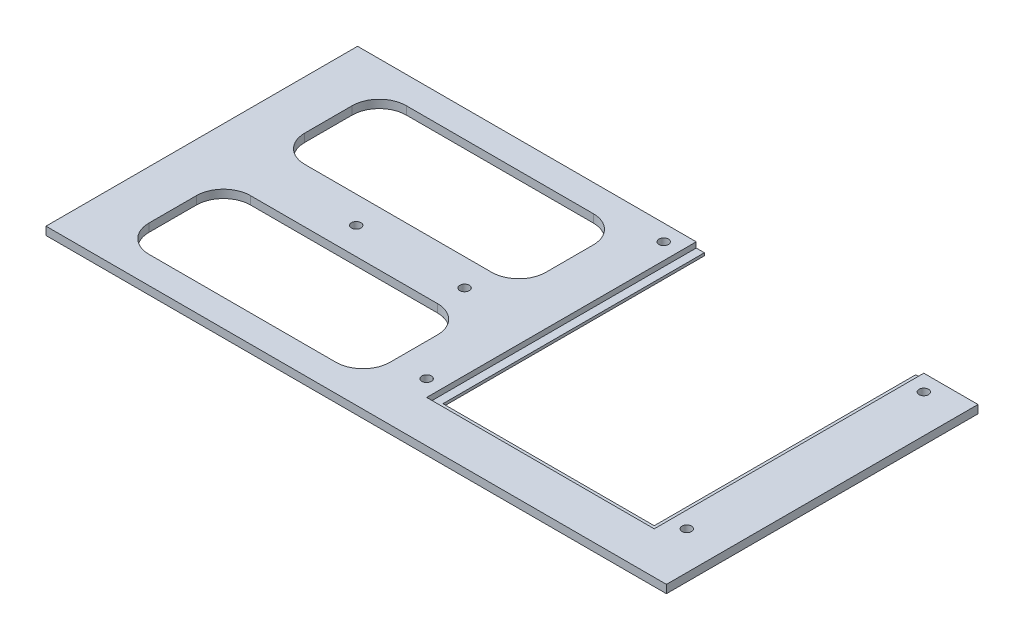
SolidWorks part; units mm, degrees
ref_plane "前视基准面" through (0, 0, 0) normal (0, 0, 1) x (1, 0, 0)
ref_plane "上视基准面" through (0, 0, 0) normal (0, 1, 0) x (1, 0, 0)
ref_plane "右视基准面" through (0, 0, 0) normal (1, 0, 0) x (0, 0, -1)
sketch "草图1" plane through (0, 0, 0) normal (0, 1, 0) x (1, 0, 0)
  line L1 (-121.6849, 60.5367) -> (107.3151, 60.5367)
  line L2 (-121.6849, 60.5367) -> (-121.6849, -54.4633)
  line L3 (-121.6849, -54.4633) -> (107.3151, -54.4633)
  line L4 (107.3151, 60.5367) -> (107.3151, -54.4633)
  dimension "D1" = 229
  dimension "D2" = 115
extrude "凸台-拉伸1" add sketch "草图1" along normal blind 3
sketch "草图2" plane through (0, 3, 0) normal (0, 1, 0) x (1, 0, 0)
  line L0 (107.3151, -54.4633) -> (107.3151, 60.5367) construction
  line L1 (3.3151, 45.0367) -> (87.3151, 45.0367) construction
  line L2 (3.3151, 45.0367) -> (3.3151, -38.9633) construction
  line L3 (3.3151, -38.9633) -> (87.3151, -38.9633) construction
  line L4 (87.3151, 45.0367) -> (87.3151, -38.9633) construction
  line L5 (107.3151, 60.5367) -> (-121.6849, 60.5367) construction
  line L10 (3.3151, 45.0367) -> (6.3151, 45.0367)
  line L18 (3.3151, -38.9633) -> (87.3151, -38.9633)
  line L19 (3.3151, -38.9633) -> (3.3151, 60.5367)
  line L20 (3.3151, 60.5367) -> (87.3151, 60.5367)
  line L21 (87.3151, -38.9633) -> (87.3151, 60.5367)
  point P4 (87.3151, 3.0367)
  point P5 (107.3151, 3.0367)
  dimension "D1" = 84
  dimension "D2" = 84
  dimension "D3" = 20
extrude "切除-拉伸2" cut sketch "草图2" against normal blind 2
sketch "草图4" plane through (0, 1, 0) normal (0, 1, 0) x (1, 0, 0)
  line L0 (87.3151, 60.5367) -> (3.3151, 60.5367) construction
  line L1 (6.3151, 60.5367) -> (84.3151, 60.5367)
  line L2 (6.3151, 60.5367) -> (6.3151, -35.9633)
  line L3 (6.3151, -35.9633) -> (84.3151, -35.9633)
  line L4 (84.3151, 60.5367) -> (84.3151, -35.9633)
  line L5 (3.3151, -38.9633) -> (3.3151, 60.5367) construction
  line L6 (87.3151, -38.9633) -> (87.3151, 60.5367) construction
  line L7 (3.3151, -38.9633) -> (87.3151, -38.9633) construction
  dimension "D1" = 3
  dimension "D2" = 3
  dimension "D3" = 3
extrude "切除-拉伸3" cut sketch "草图4" against normal blind 2
sketch "草图5" plane through (0, 3, 0) normal (0, 1, 0) x (1, 0, 0)
  line L0 (-121.6849, 60.5367) -> (-121.6849, -54.4633) construction
  line L2 (-93.6849, 50.5367) -> (-24.6849, 50.5367)
  line L3 (-103.6849, 40.5367) -> (-103.6849, 23.0367)
  line L4 (-93.6849, 13.0367) -> (-24.6849, 13.0367)
  line L5 (-14.6849, 40.5367) -> (-14.6849, 23.0367)
  line L6 (-93.6849, -6.9633) -> (-24.6849, -6.9633)
  line L7 (-103.6849, -16.9633) -> (-103.6849, -34.4633)
  line L8 (-93.6849, -44.4633) -> (-24.6849, -44.4633)
  line L9 (-14.6849, -16.9633) -> (-14.6849, -34.4633)
  line L10 (3.3151, -38.9633) -> (3.3151, 60.5367) construction
  line L11 (3.3151, 60.5367) -> (-121.6849, 60.5367) construction
  line L12 (-121.6849, -54.4633) -> (107.3151, -54.4633) construction
  line L13 (87.3151, -38.9633) -> (87.3151, 60.5367) construction
  line L14 (3.3151, -38.9633) -> (87.3151, -38.9633) construction
  circle A0 centre (-64.6849, 3.0367) radius 1.75
  circle A1 centre (-24.6849, 3.0367) radius 1.75
  arc A2 (-24.6849, 50.5367) -> (-14.6849, 40.5367) centre (-24.6849, 40.5367) cw
  arc A3 (-14.6849, 23.0367) -> (-24.6849, 13.0367) centre (-24.6849, 23.0367) cw
  arc A4 (-93.6849, 13.0367) -> (-103.6849, 23.0367) centre (-93.6849, 23.0367) cw
  arc A5 (-103.6849, 40.5367) -> (-93.6849, 50.5367) centre (-93.6849, 40.5367) cw
  arc A6 (-24.6849, -6.9633) -> (-14.6849, -16.9633) centre (-24.6849, -16.9633) cw
  arc A7 (-14.6849, -34.4633) -> (-24.6849, -44.4633) centre (-24.6849, -34.4633) cw
  arc A8 (-93.6849, -44.4633) -> (-103.6849, -34.4633) centre (-93.6849, -34.4633) cw
  arc A9 (-103.6849, -16.9633) -> (-93.6849, -6.9633) centre (-93.6849, -16.9633) cw
  circle A10 centre (-2.6849, 54.5367) radius 1.75
  circle A11 centre (93.3151, 54.5367) radius 1.75
  circle A12 centre (93.3151, -32.9633) radius 1.75
  circle A13 centre (-2.6849, -32.9633) radius 1.75
  point P6 (-121.6849, 3.0367)
  point P45 (-64.9694, 3.0367)
  point P46 (-66.9496, 3.0367)
  point P47 (0, 0)
  point P48 (0, 0)
  point P49 (0, 0)
  point P50 (0, 0)
  dimension "D2" = 10
  dimension "D3" = 10
  dimension "D12" = 6
  dimension "D1" = 40
  dimension "D4" = 18
  dimension "D5" = 18
  dimension "D6" = 10
  dimension "D7" = 18
  dimension "D8" = 18
  dimension "D9" = 10
  dimension "D10" = 10
  dimension "D11" = 10
  dimension "D13" = 6
  dimension "D14" = 6
  dimension "D15" = 6
extrude "切除-拉伸4" cut sketch "草图5" against normal blind 3
